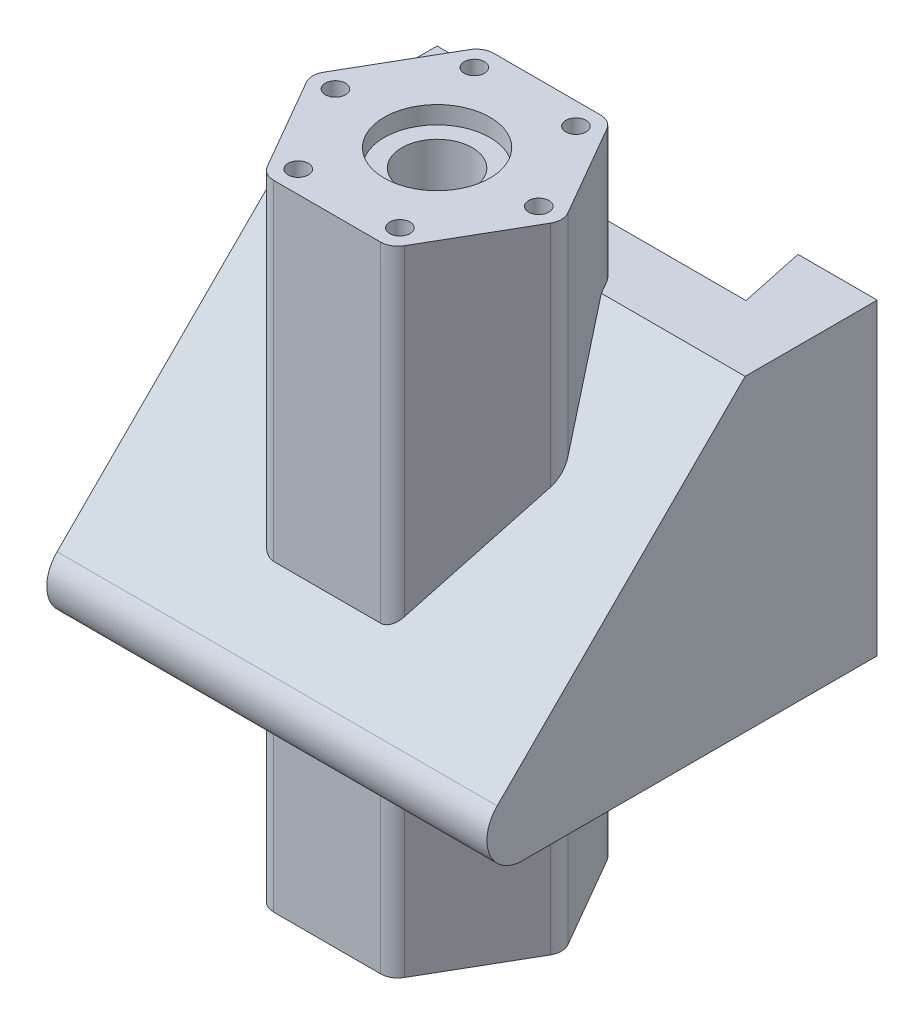
SolidWorks part; units mm, degrees
ref_plane "Front Plane" through (0, 0, 0) normal (0, 0, 1) x (1, 0, 0)
ref_plane "Top Plane" through (0, 0, 0) normal (0, 1, 0) x (1, 0, 0)
ref_plane "Right Plane" through (0, 0, 0) normal (1, 0, 0) x (0, 0, -1)
sketch "Sketch1" plane through (0, 0, 0) normal (1, 0, 0) x (0, 0, -1)
  line L0 (0, 0) -> (-40.3431, 0)
  line L1 (-43.1716, 6.8284) -> (-15, 35)
  line L2 (-15, 35) -> (0, 35)
  line L3 (0, 35) -> (0, 0)
  arc A0 (-40.3431, 0) -> (-43.1716, 6.8284) centre (-40.3431, 4) cw
  point P7 (-50, 0)
  dimension "D4" = 4
  dimension "D1" = 50
  dimension "D2" = 35
  dimension "D3" = 45
extrude "Boss-Extrude1" add sketch "Sketch1" along normal mid plane 50
sketch "Sketch2" plane through (0, 0, 0) normal (0, 1, 0) x (1, 0, 0)
  line L0 (0, -25) -> (-34.3691, -25) construction
  line L1 (-7.7942, -13.5) -> (-13.8564, -24)
  line L2 (-13.8564, -26) -> (-7.7942, -36.5)
  line L3 (-6.0622, -37.5) -> (6.0622, -37.5)
  line L4 (7.7942, -36.5) -> (13.8564, -26)
  line L5 (13.8564, -24) -> (7.7942, -13.5)
  line L6 (6.0622, -12.5) -> (-6.0622, -12.5)
  circle A0 centre (0, -25) radius 12.5 construction
  arc A1 (-7.7942, -13.5) -> (-6.0622, -12.5) centre (-6.0622, -14.5) cw
  arc A2 (7.7942, -13.5) -> (6.0622, -12.5) centre (6.0622, -14.5) ccw
  arc A3 (13.8564, -26) -> (13.8564, -24) centre (12.1244, -25) ccw
  arc A4 (6.0622, -37.5) -> (7.7942, -36.5) centre (6.0622, -35.5) ccw
  arc A5 (-7.7942, -36.5) -> (-6.0622, -37.5) centre (-6.0622, -35.5) ccw
  arc A6 (-13.8564, -24) -> (-13.8564, -26) centre (-12.1244, -25) ccw
  point P1 (0, 0)
  point P23 (-14.4338, -25)
  dimension "D3" = 2
  dimension "D1" = 25
  dimension "D2" = 25
extrude "Boss-Extrude2" add sketch "Sketch2" along normal offset from surface 15 and the other way blind 22 up to face at (0, 35, 7.5) offset beyond the face yes
sketch "Sketch3" plane through (0, 50, 0) normal (0, 1, 0) x (1, 0, 0)
  circle A0 centre (0, -25) radius 4
  dimension "D2" = 8
  dimension "D1" = 25
extrude "Cut-Extrude1" cut sketch "Sketch3" against normal through all both and the other way through all
sketch "Sketch4" plane through (0, 50, 0) normal (0, 1, 0) x (1, 0, 0)
  circle A0 centre (0, -25) radius 6
  dimension "D1" = 12
extrude "Cut-Extrude2" cut sketch "Sketch4" against normal blind 2
sketch "Sketch5" plane through (0, 35, 0) normal (0, 1, 0) x (1, 0, 0)
  line L0 (-17.5942, -7.5) -> (17.5942, -7.5)
  line L1 (17.5942, -7.5) -> (16, 0)
  line L2 (16, 0) -> (-16, 0)
  line L3 (-16, 0) -> (-17.5942, -7.5)
  line L4 (25, 0) -> (-25, 0) construction
  line L5 (25, 0) -> (25, -15) construction
  point P7 (24.2321, -7.5)
  point P8 (17.6672, 2.5388)
  point P9 (19.443, -7.5)
  point P12 (18.2591, -7.5)
  dimension "D1" = 7.5
  dimension "D2" = 78
  dimension "D3" = 32
  dimension "D4" = 9
  dimension "D5" = 78
extrude "Cut-Extrude3" cut sketch "Sketch5" against normal through all both and the other way through all
hole_wizard "Ø2.3 (2.3) Diameter Hole1" positions "Sketch6" profile "Sketch7" hole size "Ø2.3" standard "ANSI Metric"
sketch "Sketch6" plane through (0, 50, 0) normal (0, 1, 0) x (1, 0, 0)
  line L0 (0, -25) -> (-5.7735, -15) construction
  line L2 (0, -25) -> (-11.547, -25) construction
  circle A0 centre (0, -25) radius 11.547 construction
  point P0 (-11.547, -25)
  point P2 (-5.7735, -15)
  point P4 (5.7735, -15)
  point P6 (11.547, -25)
  point P8 (5.7735, -35)
  point P10 (-5.7735, -35)
  point P44 (5.8865, -14.8042)
  dimension "D1" = 60
  dimension "D2" = 15
sketch "Sketch7" plane through (-11.547, 50, 25) normal (1, 0, 0) x (0, 0, 1)
  line L0 (0, 0) -> (0, 4.691)
  line L1 (0, 4.691) -> (1.15, 4)
  line L2 (1.15, 4) -> (1.15, 0)
  line L5 (1.15, 0) -> (0, 0)
  line L10 (0, 4.691) -> (-1.15, 4) construction
  line L11 (0, -6.35) -> (0, 107.95) construction
  dimension "Hole Dia." = 2.3
  dimension "Hole Depth" = 4
  dimension "Drill Angle" = 118
equation "\"D5@Sketch5\"=\"D2@Sketch5\""
